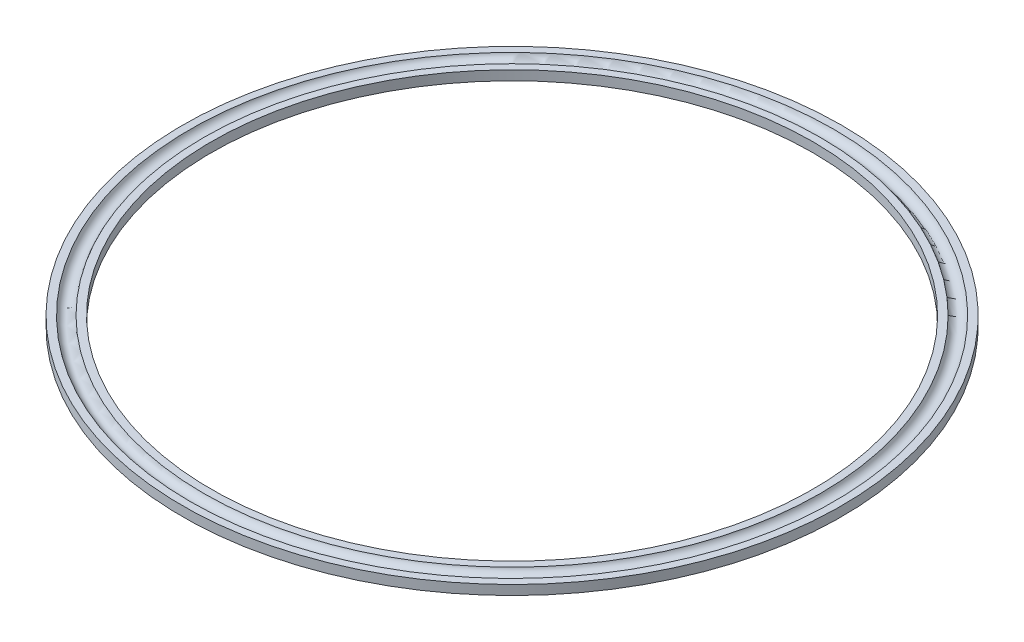
SolidWorks part; units mm, degrees
material "6061 Alloy"
ref_plane "Front Plane" through (0, 0, 0) normal (0, 0, 1) x (1, 0, 0)
ref_plane "Top Plane" through (0, 0, 0) normal (0, 1, 0) x (1, 0, 0)
ref_plane "Right Plane" through (0, 0, 0) normal (1, 0, 0) x (0, 0, -1)
sketch "Sketch1" plane through (0, 0, 0) normal (0, 0, 1) x (1, 0, 0)
  line L0 (0, 0) -> (0, 45377.1741) construction
  line L1 (-100.0125, 0) -> (-109.5375, 0)
  line L2 (-109.5375, 0) -> (-109.5375, 3.175)
  line L3 (-109.5375, 3.175) -> (-107.07, 3.175)
  line L4 (-100.0125, 0) -> (-100.0125, 3.175)
  line L5 (-100.0125, 3.175) -> (-102.48, 3.175)
  line L6 (-104.775, 0) -> (-104.775, 3.81) construction
  arc A0 (-107.07, 3.175) -> (-102.48, 3.175) centre (-104.775, 3.81) ccw
  arc A1 (-102.48, 3.175) -> (-107.07, 3.175) centre (-104.775, 3.81) ccw construction
  point P12 (-39.5323, 3.812)
  point P13 (-35.9464, 3.6169)
  dimension "D1" = 4.7625
  dimension "D2" = 9.525
  dimension "D3" = 3.175
  dimension "D4" = 200.025
  dimension "D5" = 3.81
revolve "Revolve1" add sketch "Sketch1" angle 360 about L0
